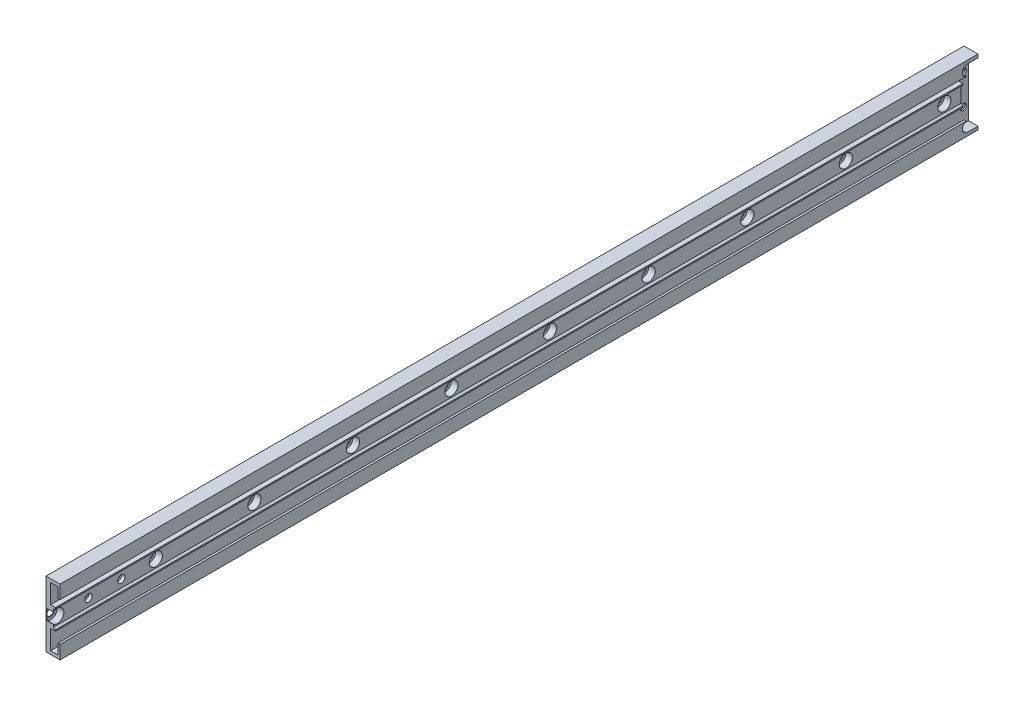
SolidWorks part; units mm, degrees
material "6061 Alloy"
ref_plane "Right Plane" through (0, 0, 0) normal (0, 0, 1) x (1, 0, 0)
ref_plane "Top Plane" through (0, 0, 0) normal (0, 1, 0) x (1, 0, 0)
ref_plane "Front Plane" through (0, 0, 0) normal (1, 0, 0) x (0, 0, -1)
sketch "Sketch1" plane through (0, 0, 0) normal (0, 0, 1) x (1, 0, 0)
  line L0 (-39.1, 20) -> (-39.1, 11.75)
  line L1 (-39.1, -20) -> (-47.625, -20)
  line L2 (-47.625, -20) -> (-47.625, 20)
  line L3 (-47.625, 20) -> (-39.1, 20)
  line L4 (-39.1, 11.75) -> (-40.375, 11.75)
  line L5 (-40.375, 11.75) -> (-40.375, 18)
  line L6 (-40.375, 18) -> (-44.875, 18)
  line L7 (-44.875, 18) -> (-44.875, 6.25)
  line L8 (-44.875, -18) -> (-40.375, -18)
  line L9 (-40.375, -18) -> (-40.375, -11.75)
  line L10 (-40.375, -11.75) -> (-39.1, -11.75)
  line L11 (-39.1, -11.75) -> (-39.1, -20)
  line L12 (-44.875, 6.25) -> (-41.875, 6.25)
  line L13 (-41.875, 6.25) -> (-41.875, 5.5)
  line L14 (-41.875, -6.25) -> (-44.875, -6.25)
  line L15 (-44.875, -6.25) -> (-44.875, -18)
  line L16 (-41.875, 5.5) -> (-43.125, 4.7783)
  line L17 (-43.125, 4.7783) -> (-43.125, -4.7783)
  line L18 (-41.875, -5.5) -> (-43.125, -4.7783)
  line L19 (-41.875, -5.5) -> (-41.875, -6.25)
  line L20 (0, 0) -> (-47.625, 0) construction
  dimension "D1" = 1.275
  dimension "D2" = 1.275
  dimension "D3" = 2
  dimension "D4" = 2
  dimension "D5" = 2.75
  dimension "D6" = 5.75
  dimension "D7" = 4.5
  dimension "D8" = 0.75
  dimension "D9" = 0.75
  dimension "D10" = 120
  dimension "D11" = 120
  dimension "D12" = 8.525
  dimension "D13" = 8.25
  dimension "D14" = 6.25
  dimension "D15" = 11.75
  dimension "D16" = 40
  dimension "D17" = 47.625
  dimension "D19" = 9.5566
extrude "Boss-Extrude1" add sketch "Sketch1" against normal blind 276.86 and the other way blind 281.94
hole_wizard "CBORE for M4 SHCS1" positions "Sketch3" profile "Sketch2" counterbore size "M4" standard "Ansi Metric" end condition through all
sketch "Sketch3" plane through (-43.125, 0, 0) normal (1, 0, 0) x (0, 0, -1)
  line L0 (-281.94, 0) -> (276.86, 0) construction
  line L1 (-281.94, -4.7783) -> (-281.94, 4.7783) construction
  line L2 (276.86, -4.7783) -> (276.86, 4.7783) construction
  point P0 (-219.59, 0)
  dimension "D1" = 62.35
sketch "Sketch2" plane through (-43.125, 0, 219.59) normal (0, 1, 0) x (0, 0, -1)
  line L0 (0, 0) -> (0, 4.5)
  line L1 (0, 4.5) -> (2.25, 4.5)
  line L3 (2.25, 4.5) -> (2.25, 4)
  line L4 (2.25, 4) -> (4, 4)
  line L5 (4, 4) -> (4, 0)
  line L7 (4, 0) -> (0, 0)
  line L11 (0, -6.35) -> (0, 107.95) construction
  dimension "Thru Hole Dia." = 4.5
  dimension "Thru Hole Depth" = 4.5
  dimension "C'Bore Dia." = 8
  dimension "C'Bore Depth" = 4
hole_wizard "CSK for M4 Flat Head Machine Screw1" positions "Sketch5" profile "Sketch4" countersink size "M4" standard "Ansi Metric" end condition through all
sketch "Sketch5" plane through (-47.625, 6.6805, -0.938) normal (1, 0, 0) x (0, 0, -1)
  line L0 (-282.878, -6.6805) -> (-241.528, -6.6805) construction
  line L1 (-282.878, -11.4588) -> (-282.878, -1.9022) construction
  point P0 (-241.528, -6.6805)
  point P1 (-261.528, -6.6805)
  dimension "D1" = 21.35
  dimension "D2" = 20
sketch "Sketch4" plane through (-47.625, 0, 240.59) normal (0, 1, 0) x (0, 0, 1)
  line L0 (0, 0) -> (0, 8.525)
  line L1 (0, 8.525) -> (2.25, 8.525)
  line L2 (2.25, 8.525) -> (2.25, 2.45)
  line L3 (2.25, 2.45) -> (4.7, 0)
  line L5 (4.7, 0) -> (0, 0)
  line L6 (-2.25, 2.45) -> (-4.7, 0) construction
  line L11 (0, -6.35) -> (0, 107.95) construction
  dimension "Thru Hole Dia." = 4.5
  dimension "Thru Hole Depth" = 8.525
  dimension "Near C'Sink Dia." = 9.4
  dimension "Near C'Sink Angle" = 90
pattern_linear "LPattern1" count 9 spacing 60 along (0, 0, -1) count 2 spacing 60 along (0, 0, 1) of "CBORE for M4 SHCS1"
hole_wizard "CSK for #6 Flat Head Machine Screw1" positions "Sketch7" profile "Sketch6" countersink size "#6" standard "Ansi Inch" end condition through all
sketch "Sketch7" plane through (-47.625, 11.9601, 21.1114) normal (1, 0, 0) x (0, 0, -1)
  line L0 (297.9714, -29.9601) -> (297.9714, -18.2101) construction
  line L1 (297.9714, -5.7101) -> (297.9714, 6.0399) construction
  line L2 (-260.8286, -18.2101) -> (297.9714, -18.2101) construction
  line L3 (-260.8286, -5.7101) -> (297.9714, -5.7101) construction
  point P0 (294.7964, -21.2101)
  point P1 (294.7964, -2.7101)
  dimension "D1" = 3.175
  dimension "D2" = 3.175
  dimension "D3" = 3
  dimension "D4" = 3
sketch "Sketch6" plane through (-47.625, -9.25, -273.685) normal (0, 1, 0) x (0, 0, 1)
  line L0 (0, 0) -> (0, 8.525)
  line L1 (0, 8.525) -> (1.8986, 8.525)
  line L2 (1.8986, 8.525) -> (1.8986, 1.892)
  line L3 (1.8986, 1.892) -> (3.5433, 0)
  line L5 (3.5433, 0) -> (0, 0)
  line L6 (-1.8986, 1.892) -> (-3.5433, 0) construction
  line L11 (0, -6.35) -> (0, 107.95) construction
  dimension "Thru Hole Dia." = 3.7973
  dimension "Thru Hole Depth" = 8.525
  dimension "Near C'Sink Dia." = 7.0866
  dimension "Near C'Sink Angle" = 82
sketch "Sketch8" plane through (-39.1, 0, 0) normal (1, 0, 0) x (0, 0, -1)
  line L0 (276.86, -20) -> (276.86, -18) construction
  line L1 (276.86, -20) -> (276.86, -11.75) construction
  line L2 (276.86, 20) -> (276.86, 18) construction
  line L3 (276.86, 11.75) -> (276.86, 20) construction
  line L4 (-281.94, 20) -> (276.86, 20) construction
  line L5 (276.86, -18) -> (270.51, -18)
  line L6 (276.86, -18) -> (276.86, 18)
  line L7 (276.86, 18) -> (270.51, 18)
  line L8 (270.51, -18) -> (270.51, 18)
  line L9 (270.51, -18) -> (270.51, -14.825) construction
  line L10 (270.51, 18) -> (270.51, 14.825) construction
  circle A0 centre (270.51, -14.825) radius 3.175
  circle A1 centre (270.51, 14.825) radius 3.175
  line M6 (276.86, -20) -> (276.86, -11.75)
  line M7 (276.86, -11.75) -> (-281.94, -11.75)
  dimension "D4" = 6.35
  dimension "D5" = 6.35
  dimension "D1" = 6.35
  dimension "D2" = 36
  dimension "D3" = 2
extrude "Cut-Extrude1" cut sketch "Sketch8" against normal up to vertex contours A1 L8 A0 L6 L7 M7 | A0 L5 M6 M7 | L8 A0 M7 | A0 L8 M7 | L8 A1 | L8 A1
